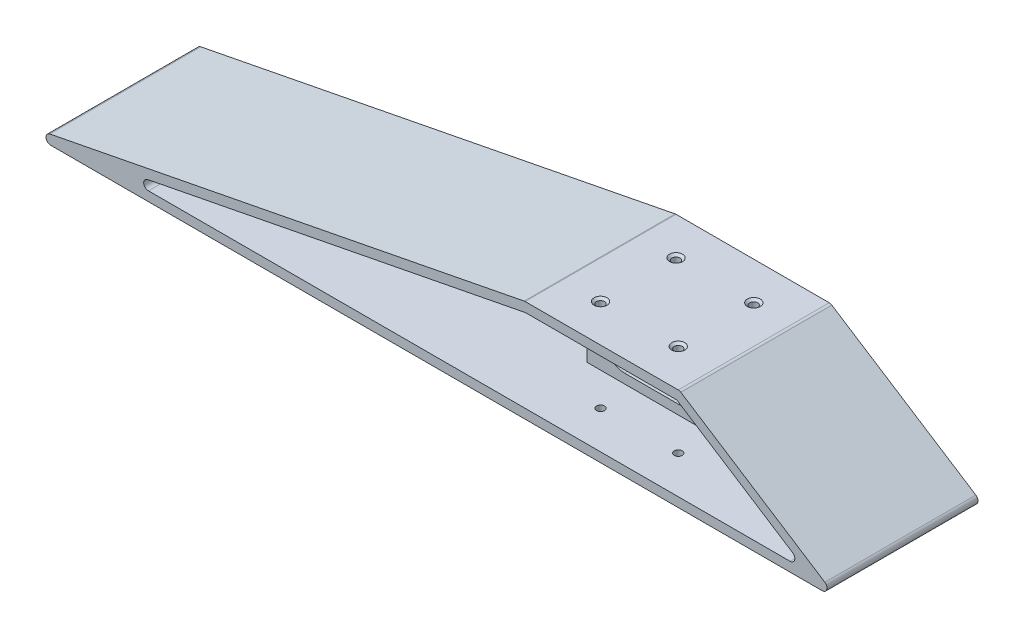
SolidWorks part; units mm, degrees
ref_plane "Front Plane" through (0, 0, 0) normal (0, 0, 1) x (1, 0, 0)
ref_plane "Top Plane" through (0, 0, 0) normal (0, 1, 0) x (1, 0, 0)
ref_plane "Right Plane" through (0, 0, 0) normal (1, 0, 0) x (0, 0, -1)
sketch "Sketch1" plane through (0, 0, 0) normal (0, 0, 1) x (1, 0, 0)
  line L0 (16.4387, 0) -> (232.3387, 0)
  line L1 (233.1965, 2.9233) -> (194.2387, 27.94)
  line L2 (194.2387, 27.94) -> (143.3117, 27.94)
  line L3 (143.3117, 27.94) -> (16.135, 3.1457)
  line L4 (143.0051, 31.115) -> (-32.8775, -3.175)
  line L5 (-32.8775, -3.175) -> (248.5692, -3.175)
  line L6 (248.5692, -3.175) -> (195.1704, 31.115)
  line L7 (195.1704, 31.115) -> (143.0051, 31.115)
  line L8 (0, 0) -> (237.7489, 0) construction
  line L9 (143.3117, 27.94) -> (0, 0) construction
  line L10 (237.7489, 0) -> (194.2387, 27.94) construction
  arc A0 (16.4387, 0) -> (16.135, 3.1457) centre (16.4387, 1.5875) cw
  arc A1 (232.3387, 0) -> (233.1965, 2.9233) centre (232.3387, 1.5875) ccw
  point P12 (0, 0)
  point P16 (0, 0)
  point P17 (0, 0)
  dimension "D6" = 1.5875
  dimension "D7" = 1.5875
  dimension "D1" = 215.9
  dimension "D2" = 50.927
  dimension "D3" = 38.1
  dimension "D4" = 27.94
  dimension "D5" = 3.175
extrude "Boss-Extrude1" add sketch "Sketch1" along normal blind 50.8
fillet "Fillet1" radius 1.5875 4 edges at (-32.8775, -3.175, 25.4) (143.0051, 31.115, 25.4) (195.1704, 31.115, 25.4) (248.5692, -3.175, 25.4)
sketch "Sketch3" plane through (0, 27.94, 0) normal (0, -1, 0) x (1, 0, 0)
  line L0 (143.3117, 50.8) -> (143.3117, 0) construction
  line L1 (143.3117, 26.9875) -> (194.2387, 26.9875)
  line L2 (143.3117, 26.9875) -> (143.3117, 23.8125)
  line L3 (143.3117, 23.8125) -> (194.2387, 23.8125)
  line L4 (194.2387, 26.9875) -> (194.2387, 23.8125)
  line L5 (194.2387, 50.8) -> (194.2387, 0) construction
  line L6 (194.2387, 25.4) -> (143.3117, 25.4) construction
  point P10 (194.2387, 25.4)
  dimension "D1" = 3.175
extrude "Boss-Extrude2" add sketch "Sketch3" along normal up to surface (27.94 mm away) up to face at (124.3887, 0, 25.4)
sketch "Sketch4" plane through (0, 0, 23.8125) normal (0, 0, -1) x (-1, 0, 0)
  line L8 (-191.0637, 24.765) -> (-191.0637, 3.175)
  line L9 (-191.0637, 3.175) -> (-146.4867, 3.175)
  line L10 (-146.4867, 3.175) -> (-146.4867, 24.765)
  line L11 (-146.4867, 24.765) -> (-191.0637, 24.765)
  line L12 (-191.0637, 24.765) -> (-191.0637, 3.175)
  line L13 (-191.0637, 3.175) -> (-146.4867, 3.175)
  line L14 (-146.4867, 3.175) -> (-146.4867, 24.765)
  line L15 (-146.4867, 24.765) -> (-191.0637, 24.765)
  dimension "D1" = 3.175
extrude "Cut-Extrude1" cut sketch "Sketch4" against normal up to surface (3.175 mm away) up to face at (168.7752, 13.97, 26.9875)
fillet "Fillet2" radius 6.35 4 edges at (146.4867, 3.175, 25.4) (146.4867, 24.765, 25.4) (191.0637, 24.765, 25.4) (191.0637, 3.175, 25.4)
sketch "Sketch6" plane through (0, 0, 26.9875) normal (0, 0, 1) x (1, 0, 0)
  line L0 (143.3117, 27.94) -> (16.135, 3.1457) construction
  line L1 (143.3117, 0) -> (140.1367, 0)
  line L2 (143.3117, 0) -> (143.3117, 27.94)
  line L4 (140.1367, 0) -> (140.1367, 27.321)
  line L5 (143.3117, 27.94) -> (140.1367, 27.321)
  line L6 (141.7242, 8.9662) -> (141.7242, 18.9738) construction
  line L7 (141.2162, 18.9738) -> (142.2322, 18.9738)
  line L8 (141.2162, 18.9738) -> (141.2162, 8.9662)
  line L9 (141.2162, 8.9662) -> (142.2322, 8.9662)
  line L10 (142.2322, 18.9738) -> (142.2322, 8.9662)
  point P13 (0, 0)
  point P14 (141.7242, 0)
  point P15 (143.3117, 13.97)
  point P16 (142.2322, 13.97)
  dimension "D1" = 3.175
  dimension "D2" = 1.016
  dimension "D3" = 10.0076
extrude "Boss-Extrude3" add sketch "Sketch6" against normal up to surface (3.175 mm away) up to face at (168.7752, 13.97, 23.8125)
sketch "Sketch7" plane through (0, 31.115, 0) normal (0, 1, 0) x (1, 0, 0)
  line L0 (-16.7425, -25.4) -> (244.0168, -25.4) construction
  line L1 (-16.7425, 0) -> (-16.7425, -50.8) construction
  line L2 (244.0168, -50.8) -> (244.0168, 0) construction
  line L3 (182.0045, -38.1) -> (182.0045, -12.7) construction
  line L4 (194.7045, -50.8) -> (194.7045, 0) construction
  line L5 (143.1584, 0) -> (143.1584, -50.8) construction
  line L6 (155.8584, -38.1) -> (155.8584, -12.7) construction
  line L7 (168.9315, -25.4) -> (168.9315, 0) construction
  line L8 (194.7045, 0) -> (143.1584, 0) construction
  point P6 (155.8584, -25.4)
  point P7 (182.0045, -25.4)
  point P11 (182.0045, -25.4)
  point P12 (182.0045, -38.1)
  point P13 (182.0045, -12.7)
  point P18 (155.8584, -12.7)
  point P21 (155.8584, -25.4)
  point P22 (155.2247, 0)
  point P23 (155.8584, -38.1)
  point P27 (168.9315, -12.7)
  point P28 (0, 0)
  point P29 (155.8785, -25.4)
  point P30 (159.4863, 0)
  point P31 (168.9315, 0)
  dimension "D1" = 12.7
  dimension "D2" = 12.7
hole_wizard "CSK for #2 Flat Head Machine Screw (100)1" positions "Sketch11" profile "Sketch9" countersink size "#2" standard "ANSI Inch" end condition through all
sketch "Sketch11" plane through (0, 31.115, 0) normal (0, 1, 0) x (1, 0, 0)
  point P0 (155.8584, -12.7)
  point P3 (182.0045, -12.7)
  point P6 (182.0045, -38.1)
  point P9 (155.8584, -38.1)
sketch "Sketch9" plane through (155.8584, 31.115, 12.7) normal (1, 0, 0) x (0, 0, 1)
  line L0 (0, 0) -> (0, 34.29)
  line L1 (0, 34.29) -> (1.3525, 34.29)
  line L2 (1.3525, 34.29) -> (1.3525, 0.698)
  line L3 (1.3525, 0.698) -> (2.1844, 0)
  line L5 (2.1844, 0) -> (0, 0)
  line L6 (-1.3525, 0.698) -> (-2.1844, 0) construction
  line L11 (0, -6.35) -> (0, 107.95) construction
  dimension "Thru Hole Dia." = 2.7051
  dimension "Thru Hole Depth" = 34.29
  dimension "Near C'Sink Dia." = 4.3688
  dimension "Near C'Sink Angle" = 100
equation "\"D2@Sketch7\"=\"D1@Sketch7\""
